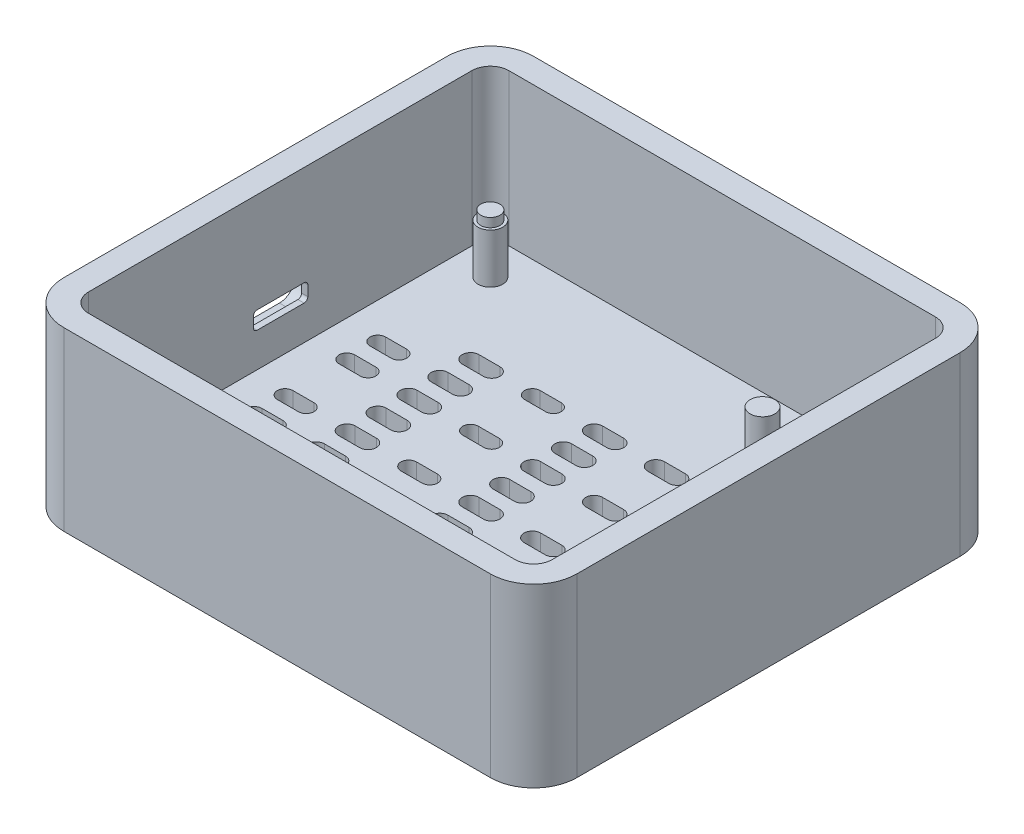
SolidWorks part; units mm, degrees
ref_plane "前视基准面" through (0, 0, 0) normal (0, 0, 1) x (1, 0, 0)
ref_plane "上视基准面" through (0, 0, 0) normal (0, 1, 0) x (1, 0, 0)
ref_plane "右视基准面" through (0, 0, 0) normal (1, 0, 0) x (0, 0, -1)
other "Configuration Table"
sketch "草图1" plane through (0, 0, 0) normal (0, 1, 0) x (1, 0, 0)
  line L1 (-34.5, 34) -> (34.5, 34)
  line L2 (-37.5, 31) -> (-37.5, -31)
  line L3 (-34.5, -34) -> (34.5, -34)
  line L4 (37.5, 31) -> (37.5, -31)
  line L5 (-37.5, 34) -> (37.5, -34) construction
  line L6 (-37.5, -34) -> (37.5, 34) construction
  arc A0 (-34.5, 34) -> (-37.5, 31) centre (-34.5, 31) ccw
  arc A1 (-37.5, -31) -> (-34.5, -34) centre (-34.5, -31) ccw
  arc A2 (34.5, -34) -> (37.5, -31) centre (34.5, -31) ccw
  arc A3 (34.5, 34) -> (37.5, 31) centre (34.5, 31) cw
  point P0 (0, 0)
  dimension "D3" = 3
  dimension "D4" = 3
  dimension "D1" = 75
  dimension "D2" = 68
extrude "凸台-拉伸1" add sketch "草图1" along normal blind 4
sketch "草图2" plane through (0, 4, 0) normal (0, 1, 0) x (1, 0, 0)
  line L0 (-1.709, 0) -> (1.709, 0) construction
  line L1 (-1.709, 1.3428) -> (1.709, 1.3428)
  line L2 (-1.709, -1.3428) -> (1.709, -1.3428)
  line L6 (18.291, 0) -> (21.709, 0) construction
  line L7 (18.291, 1.3428) -> (21.709, 1.3428)
  line L8 (18.291, -1.3428) -> (21.709, -1.3428)
  line L15 (-21.709, 0) -> (-18.291, 0) construction
  line L16 (-21.709, 1.3428) -> (-18.291, 1.3428)
  line L17 (-21.709, -1.3428) -> (-18.291, -1.3428)
  line L21 (-1.709, -5) -> (1.709, -5) construction
  line L22 (-1.709, -3.6572) -> (1.709, -3.6572)
  line L23 (-1.709, -6.3428) -> (1.709, -6.3428)
  line L24 (8.291, -5) -> (11.709, -5) construction
  line L25 (8.291, -3.6572) -> (11.709, -3.6572)
  line L26 (8.291, -6.3428) -> (11.709, -6.3428)
  line L27 (18.291, -5) -> (21.709, -5) construction
  line L28 (18.291, -3.6572) -> (21.709, -3.6572)
  line L29 (18.291, -6.3428) -> (21.709, -6.3428)
  line L30 (28.291, -5) -> (31.709, -5) construction
  line L31 (28.291, -3.6572) -> (31.709, -3.6572)
  line L32 (28.291, -6.3428) -> (31.709, -6.3428)
  line L33 (-11.709, -5) -> (-8.291, -5) construction
  line L34 (-11.709, -3.7386) -> (-8.291, -3.7386)
  line L35 (-11.709, -6.2614) -> (-8.291, -6.2614)
  line L36 (-21.709, -5) -> (-18.291, -5) construction
  line L37 (-21.709, -3.6572) -> (-18.291, -3.6572)
  line L38 (-21.709, -6.3428) -> (-18.291, -6.3428)
  line L39 (-31.709, -5) -> (-28.291, -5) construction
  line L40 (-31.709, -3.7386) -> (-28.291, -3.7386)
  line L41 (-31.709, -6.2614) -> (-28.291, -6.2614)
  line L42 (-1.709, -10) -> (1.709, -10) construction
  line L43 (-1.709, -8.6572) -> (1.709, -8.6572)
  line L44 (-1.709, -11.3428) -> (1.709, -11.3428)
  line L48 (18.291, -10) -> (21.709, -10) construction
  line L49 (18.291, -8.6572) -> (21.709, -8.6572)
  line L50 (18.291, -11.3428) -> (21.709, -11.3428)
  line L51 (28.291, -10) -> (31.709, -10) construction
  line L52 (28.291, -8.6572) -> (31.709, -8.6572)
  line L53 (28.291, -11.3428) -> (31.709, -11.3428)
  line L57 (-21.709, -10) -> (-18.291, -10) construction
  line L58 (-21.709, -8.6572) -> (-18.291, -8.6572)
  line L59 (-21.709, -11.3428) -> (-18.291, -11.3428)
  line L60 (-31.709, -10) -> (-28.291, -10) construction
  line L61 (-31.709, -8.7386) -> (-28.291, -8.7386)
  line L62 (-31.709, -11.2614) -> (-28.291, -11.2614)
  line L63 (-1.709, -15) -> (1.709, -15) construction
  line L64 (-1.709, -13.6572) -> (1.709, -13.6572)
  line L65 (-1.709, -16.3428) -> (1.709, -16.3428)
  line L66 (8.291, -15) -> (11.709, -15) construction
  line L67 (8.291, -13.6572) -> (11.709, -13.6572)
  line L68 (8.291, -16.3428) -> (11.709, -16.3428)
  line L69 (18.291, -15) -> (21.709, -15) construction
  line L70 (18.291, -13.6572) -> (21.709, -13.6572)
  line L71 (18.291, -16.3428) -> (21.709, -16.3428)
  line L75 (-11.709, -15) -> (-8.291, -15) construction
  line L76 (-11.709, -13.7386) -> (-8.291, -13.7386)
  line L77 (-11.709, -16.2614) -> (-8.291, -16.2614)
  line L78 (-21.709, -15) -> (-18.291, -15) construction
  line L79 (-21.709, -13.6572) -> (-18.291, -13.6572)
  line L80 (-21.709, -16.3428) -> (-18.291, -16.3428)
  line L84 (-1.709, 5) -> (1.709, 5) construction
  line L85 (-1.709, 6.3428) -> (1.709, 6.3428)
  line L86 (-1.709, 3.6572) -> (1.709, 3.6572)
  line L87 (8.291, 5) -> (11.709, 5) construction
  line L88 (8.291, 6.3428) -> (11.709, 6.3428)
  line L89 (8.291, 3.6572) -> (11.709, 3.6572)
  line L90 (18.291, 5) -> (21.709, 5) construction
  line L91 (18.291, 6.3428) -> (21.709, 6.3428)
  line L92 (18.291, 3.6572) -> (21.709, 3.6572)
  line L93 (28.291, 5) -> (31.709, 5) construction
  line L94 (28.291, 6.3428) -> (31.709, 6.3428)
  line L95 (28.291, 3.6572) -> (31.709, 3.6572)
  line L96 (-11.709, 5) -> (-8.291, 5) construction
  line L97 (-11.709, 6.2614) -> (-8.291, 6.2614)
  line L98 (-11.709, 3.7386) -> (-8.291, 3.7386)
  line L99 (-21.709, 5) -> (-18.291, 5) construction
  line L100 (-21.709, 6.3428) -> (-18.291, 6.3428)
  line L101 (-21.709, 3.6572) -> (-18.291, 3.6572)
  line L102 (-31.709, 5) -> (-28.291, 5) construction
  line L103 (-31.709, 6.2614) -> (-28.291, 6.2614)
  line L104 (-31.709, 3.7386) -> (-28.291, 3.7386)
  line L105 (-1.709, 10) -> (1.709, 10) construction
  line L106 (-1.709, 11.3428) -> (1.709, 11.3428)
  line L107 (-1.709, 8.6572) -> (1.709, 8.6572)
  line L111 (18.291, 10) -> (21.709, 10) construction
  line L112 (18.291, 11.3428) -> (21.709, 11.3428)
  line L113 (18.291, 8.6572) -> (21.709, 8.6572)
  line L114 (28.291, 10) -> (31.709, 10) construction
  line L115 (28.291, 11.3428) -> (31.709, 11.3428)
  line L116 (28.291, 8.6572) -> (31.709, 8.6572)
  line L120 (-21.709, 10) -> (-18.291, 10) construction
  line L121 (-21.709, 11.3428) -> (-18.291, 11.3428)
  line L122 (-21.709, 8.6572) -> (-18.291, 8.6572)
  line L123 (-31.709, 10) -> (-28.291, 10) construction
  line L124 (-31.709, 11.2614) -> (-28.291, 11.2614)
  line L125 (-31.709, 8.7386) -> (-28.291, 8.7386)
  line L126 (-1.709, 15) -> (1.709, 15) construction
  line L127 (-1.709, 16.3428) -> (1.709, 16.3428)
  line L128 (-1.709, 13.6572) -> (1.709, 13.6572)
  line L129 (8.291, 15) -> (11.709, 15) construction
  line L130 (8.291, 16.3428) -> (11.709, 16.3428)
  line L131 (8.291, 13.6572) -> (11.709, 13.6572)
  line L132 (18.291, 15) -> (21.709, 15) construction
  line L133 (18.291, 16.3428) -> (21.709, 16.3428)
  line L134 (18.291, 13.6572) -> (21.709, 13.6572)
  line L138 (-11.709, 15) -> (-8.291, 15) construction
  line L139 (-11.709, 16.2614) -> (-8.291, 16.2614)
  line L140 (-11.709, 13.7386) -> (-8.291, 13.7386)
  line L141 (-21.709, 15) -> (-18.291, 15) construction
  line L142 (-21.709, 16.3428) -> (-18.291, 16.3428)
  line L143 (-21.709, 13.6572) -> (-18.291, 13.6572)
  line L164 (28.291, 0) -> (31.709, 0) construction
  line L165 (28.291, 1.3428) -> (31.709, 1.3428)
  line L166 (28.291, -1.3428) -> (31.709, -1.3428)
  line L167 (8.291, 0) -> (11.709, 0) construction
  line L168 (8.291, 1.3428) -> (11.709, 1.3428)
  line L169 (8.291, -1.3428) -> (11.709, -1.3428)
  line L170 (-11.709, 0) -> (-8.291, 0) construction
  line L171 (-11.709, 1.3428) -> (-8.291, 1.3428)
  line L172 (-11.709, -1.3428) -> (-8.291, -1.3428)
  line L173 (-31.709, 0) -> (-28.291, 0) construction
  line L174 (-31.709, 1.3428) -> (-28.291, 1.3428)
  line L175 (-31.709, -1.3428) -> (-28.291, -1.3428)
  line L176 (28.291, 0) -> (31.709, 0) construction
  line L177 (28.291, 1.3428) -> (31.709, 1.3428)
  line L178 (28.291, -1.3428) -> (31.709, -1.3428)
  line L179 (8.291, 0) -> (11.709, 0) construction
  line L180 (8.291, 1.3428) -> (11.709, 1.3428)
  line L181 (8.291, -1.3428) -> (11.709, -1.3428)
  line L182 (-11.709, 0) -> (-8.291, 0) construction
  line L183 (-11.709, 1.3428) -> (-8.291, 1.3428)
  line L184 (-11.709, -1.3428) -> (-8.291, -1.3428)
  line L185 (-31.709, 0) -> (-28.291, 0) construction
  line L186 (-31.709, 1.3428) -> (-28.291, 1.3428)
  line L187 (-31.709, -1.3428) -> (-28.291, -1.3428)
  arc A0 (-1.709, 1.3428) -> (-1.709, -1.3428) centre (-1.709, 0) ccw
  arc A1 (1.709, -1.3428) -> (1.709, 1.3428) centre (1.709, 0) ccw
  arc A4 (18.291, 1.3428) -> (18.291, -1.3428) centre (18.291, 0) ccw
  arc A5 (21.709, -1.3428) -> (21.709, 1.3428) centre (21.709, 0) ccw
  arc A10 (-21.709, 1.3428) -> (-21.709, -1.3428) centre (-21.709, 0) ccw
  arc A11 (-18.291, -1.3428) -> (-18.291, 1.3428) centre (-18.291, 0) ccw
  arc A14 (-1.709, -3.6572) -> (-1.709, -6.3428) centre (-1.709, -5) ccw
  arc A15 (1.709, -6.3428) -> (1.709, -3.6572) centre (1.709, -5) ccw
  arc A16 (8.291, -3.6572) -> (8.291, -6.3428) centre (8.291, -5) ccw
  arc A17 (11.709, -6.3428) -> (11.709, -3.6572) centre (11.709, -5) ccw
  arc A18 (18.291, -3.6572) -> (18.291, -6.3428) centre (18.291, -5) ccw
  arc A19 (21.709, -6.3428) -> (21.709, -3.6572) centre (21.709, -5) ccw
  arc A20 (28.291, -3.6572) -> (28.291, -6.3428) centre (28.291, -5) ccw
  arc A21 (31.709, -6.3428) -> (31.709, -3.6572) centre (31.709, -5) ccw
  arc A22 (-11.709, -3.7386) -> (-11.709, -6.2614) centre (-11.709, -5) ccw
  arc A23 (-8.291, -6.2614) -> (-8.291, -3.7386) centre (-8.291, -5) ccw
  arc A24 (-21.709, -3.6572) -> (-21.709, -6.3428) centre (-21.709, -5) ccw
  arc A25 (-18.291, -6.3428) -> (-18.291, -3.6572) centre (-18.291, -5) ccw
  arc A26 (-31.709, -3.7386) -> (-31.709, -6.2614) centre (-31.709, -5) ccw
  arc A27 (-28.291, -6.2614) -> (-28.291, -3.7386) centre (-28.291, -5) ccw
  arc A28 (-1.709, -8.6572) -> (-1.709, -11.3428) centre (-1.709, -10) ccw
  arc A29 (1.709, -11.3428) -> (1.709, -8.6572) centre (1.709, -10) ccw
  arc A32 (18.291, -8.6572) -> (18.291, -11.3428) centre (18.291, -10) ccw
  arc A33 (21.709, -11.3428) -> (21.709, -8.6572) centre (21.709, -10) ccw
  arc A34 (28.291, -8.6572) -> (28.291, -11.3428) centre (28.291, -10) ccw
  arc A35 (31.709, -11.3428) -> (31.709, -8.6572) centre (31.709, -10) ccw
  arc A38 (-21.709, -8.6572) -> (-21.709, -11.3428) centre (-21.709, -10) ccw
  arc A39 (-18.291, -11.3428) -> (-18.291, -8.6572) centre (-18.291, -10) ccw
  arc A40 (-31.709, -8.7386) -> (-31.709, -11.2614) centre (-31.709, -10) ccw
  arc A41 (-28.291, -11.2614) -> (-28.291, -8.7386) centre (-28.291, -10) ccw
  arc A42 (-1.709, -13.6572) -> (-1.709, -16.3428) centre (-1.709, -15) ccw
  arc A43 (1.709, -16.3428) -> (1.709, -13.6572) centre (1.709, -15) ccw
  arc A44 (8.291, -13.6572) -> (8.291, -16.3428) centre (8.291, -15) ccw
  arc A45 (11.709, -16.3428) -> (11.709, -13.6572) centre (11.709, -15) ccw
  arc A46 (18.291, -13.6572) -> (18.291, -16.3428) centre (18.291, -15) ccw
  arc A47 (21.709, -16.3428) -> (21.709, -13.6572) centre (21.709, -15) ccw
  arc A50 (-11.709, -13.7386) -> (-11.709, -16.2614) centre (-11.709, -15) ccw
  arc A51 (-8.291, -16.2614) -> (-8.291, -13.7386) centre (-8.291, -15) ccw
  arc A52 (-21.709, -13.6572) -> (-21.709, -16.3428) centre (-21.709, -15) ccw
  arc A53 (-18.291, -16.3428) -> (-18.291, -13.6572) centre (-18.291, -15) ccw
  arc A56 (-1.709, 6.3428) -> (-1.709, 3.6572) centre (-1.709, 5) ccw
  arc A57 (1.709, 3.6572) -> (1.709, 6.3428) centre (1.709, 5) ccw
  arc A58 (8.291, 6.3428) -> (8.291, 3.6572) centre (8.291, 5) ccw
  arc A59 (11.709, 3.6572) -> (11.709, 6.3428) centre (11.709, 5) ccw
  arc A60 (18.291, 6.3428) -> (18.291, 3.6572) centre (18.291, 5) ccw
  arc A61 (21.709, 3.6572) -> (21.709, 6.3428) centre (21.709, 5) ccw
  arc A62 (28.291, 6.3428) -> (28.291, 3.6572) centre (28.291, 5) ccw
  arc A63 (31.709, 3.6572) -> (31.709, 6.3428) centre (31.709, 5) ccw
  arc A64 (-11.709, 6.2614) -> (-11.709, 3.7386) centre (-11.709, 5) ccw
  arc A65 (-8.291, 3.7386) -> (-8.291, 6.2614) centre (-8.291, 5) ccw
  arc A66 (-21.709, 6.3428) -> (-21.709, 3.6572) centre (-21.709, 5) ccw
  arc A67 (-18.291, 3.6572) -> (-18.291, 6.3428) centre (-18.291, 5) ccw
  arc A68 (-31.709, 6.2614) -> (-31.709, 3.7386) centre (-31.709, 5) ccw
  arc A69 (-28.291, 3.7386) -> (-28.291, 6.2614) centre (-28.291, 5) ccw
  arc A70 (-1.709, 11.3428) -> (-1.709, 8.6572) centre (-1.709, 10) ccw
  arc A71 (1.709, 8.6572) -> (1.709, 11.3428) centre (1.709, 10) ccw
  arc A74 (18.291, 11.3428) -> (18.291, 8.6572) centre (18.291, 10) ccw
  arc A75 (21.709, 8.6572) -> (21.709, 11.3428) centre (21.709, 10) ccw
  arc A76 (28.291, 11.3428) -> (28.291, 8.6572) centre (28.291, 10) ccw
  arc A77 (31.709, 8.6572) -> (31.709, 11.3428) centre (31.709, 10) ccw
  arc A80 (-21.709, 11.3428) -> (-21.709, 8.6572) centre (-21.709, 10) ccw
  arc A81 (-18.291, 8.6572) -> (-18.291, 11.3428) centre (-18.291, 10) ccw
  arc A82 (-31.709, 11.2614) -> (-31.709, 8.7386) centre (-31.709, 10) ccw
  arc A83 (-28.291, 8.7386) -> (-28.291, 11.2614) centre (-28.291, 10) ccw
  arc A84 (-1.709, 16.3428) -> (-1.709, 13.6572) centre (-1.709, 15) ccw
  arc A85 (1.709, 13.6572) -> (1.709, 16.3428) centre (1.709, 15) ccw
  arc A86 (8.291, 16.3428) -> (8.291, 13.6572) centre (8.291, 15) ccw
  arc A87 (11.709, 13.6572) -> (11.709, 16.3428) centre (11.709, 15) ccw
  arc A88 (18.291, 16.3428) -> (18.291, 13.6572) centre (18.291, 15) ccw
  arc A89 (21.709, 13.6572) -> (21.709, 16.3428) centre (21.709, 15) ccw
  arc A92 (-11.709, 16.2614) -> (-11.709, 13.7386) centre (-11.709, 15) ccw
  arc A93 (-8.291, 13.7386) -> (-8.291, 16.2614) centre (-8.291, 15) ccw
  arc A94 (-21.709, 16.3428) -> (-21.709, 13.6572) centre (-21.709, 15) ccw
  arc A95 (-18.291, 13.6572) -> (-18.291, 16.3428) centre (-18.291, 15) ccw
  arc A122 (28.291, 1.3428) -> (28.291, -1.3428) centre (28.291, 0) ccw
  arc A123 (31.709, -1.3428) -> (31.709, 1.3428) centre (31.709, 0) ccw
  arc A124 (8.291, 1.3428) -> (8.291, -1.3428) centre (8.291, 0) ccw
  arc A125 (11.709, -1.3428) -> (11.709, 1.3428) centre (11.709, 0) ccw
  arc A126 (-11.709, 1.3428) -> (-11.709, -1.3428) centre (-11.709, 0) ccw
  arc A127 (-8.291, -1.3428) -> (-8.291, 1.3428) centre (-8.291, 0) ccw
  arc A128 (-31.709, 1.3428) -> (-31.709, -1.3428) centre (-31.709, 0) ccw
  arc A129 (-28.291, -1.3428) -> (-28.291, 1.3428) centre (-28.291, 0) ccw
  point P2 (0, 0)
  point P12 (30, 0)
  point P19 (20, 0)
  point P33 (10, 0)
  point P40 (-20, 0)
  point P47 (-10, 0)
  point P53 (0, -5)
  point P60 (10, -5)
  point P67 (20, -5)
  point P74 (30, -5)
  point P81 (-10, -5)
  point P88 (-20, -5)
  point P95 (-30, -5)
  point P102 (0, -10)
  point P116 (20, -10)
  point P123 (30, -10)
  point P137 (-20, -10)
  point P144 (-30, -10)
  point P151 (0, -15)
  point P158 (10, -15)
  point P165 (20, -15)
  point P170 (0, 0)
  point P173 (-30, -15)
  point P179 (-10, -15)
  point P186 (-20, -15)
  point P191 (0, 0)
  point P194 (30, 15)
  point P200 (0, 5)
  point P207 (10, 5)
  point P214 (20, 5)
  point P221 (30, 5)
  point P228 (-10, 5)
  point P235 (-20, 5)
  point P242 (-30, 5)
  point P249 (0, 10)
  point P263 (20, 10)
  point P270 (30, 10)
  point P284 (-20, 10)
  point P291 (-30, 10)
  point P298 (0, 15)
  point P305 (10, 15)
  point P312 (20, 15)
  point P319 (-30, 0)
  point P326 (-10, 15)
  point P333 (-20, 15)
  point P340 (30, -15)
  point P346 (-30, 15)
  point P355 (30, 0)
  point P362 (10, 0)
  point P369 (-10, 0)
  point P376 (-30, 0)
  point P383 (30, 0)
  point P390 (10, 0)
  point P397 (-10, 0)
  point P404 (-30, 0)
  dimension "D1" = 4
  dimension "D2" = 4
  dimension "D3" = 4
  dimension "D4" = 4
extrude "切除-拉伸1" cut sketch "草图2" against normal blind 65
sketch "草图7" plane through (0, 4, 0) normal (0, 1, 0) x (1, 0, 0)
  line L1 (-36.6213, 33.1213) -> (-31.6213, 33.1213) construction
  line L2 (-36.6213, 33.1213) -> (-36.6213, 28.1213) construction
  line L3 (-36.6213, 28.1213) -> (-31.6213, 28.1213) construction
  line L4 (-31.6213, 33.1213) -> (-31.6213, 28.1213) construction
  line L5 (-36.6213, -33.1213) -> (-31.6213, -33.1213) construction
  line L6 (-36.6213, -33.1213) -> (-36.6213, -28.1213) construction
  line L7 (-36.6213, -28.1213) -> (-31.6213, -28.1213) construction
  line L8 (-31.6213, -33.1213) -> (-31.6213, -28.1213) construction
  arc A0 (-34.5, 34) -> (-37.5, 31) centre (-34.5, 31) ccw construction
  circle A1 centre (-31.6213, 28.1213) radius 2
  arc A2 (-37.5, -31) -> (-34.5, -34) centre (-34.5, -31) ccw construction
  circle A3 centre (-31.6213, -28.1213) radius 2
  dimension "D3" = 5
  dimension "D1" = 5
  dimension "D2" = 5
  dimension "D4" = 5
extrude "凸台-拉伸4" add sketch "草图7" along normal blind 8
sketch "草图8" plane through (0, 12, 0) normal (0, 1, 0) x (1, 0, 0)
  circle A0 centre (-31.6213, -28.1213) radius 1.55
extrude "凸台-拉伸5" add sketch "草图8" along normal blind 1.4618
sketch "草图9" plane through (0, 12, 0) normal (0, 1, 0) x (1, 0, 0)
  circle A0 centre (-31.6213, 28.1213) radius 1.55
extrude "凸台-拉伸6" add sketch "草图9" along normal blind 1.4512
sketch "草图10" plane through (0, 4, 0) normal (0, 1, 0) x (1, 0, 0)
  line L0 (37.5, -31) -> (37.5, 31) construction
  circle A0 centre (16.546, -27.0481) radius 2
  circle A1 centre (16.546, 23.9759) radius 2
  dimension "D1" = 20.954
  dimension "D2" = 20.954
extrude "凸台-拉伸7" add sketch "草图10" along normal blind 8
sketch "草图11" plane through (0, 0, 0) normal (0, -1, 0) x (1, 0, 0)
  line L4 (-34.5, -38) -> (34.5, -38)
  line L5 (41.5, -31) -> (41.5, 31)
  line L6 (34.5, 38) -> (-34.5, 38)
  line L7 (-41.5, 31) -> (-41.5, -31)
  line L8 (-34.5, -34) -> (34.5, -34)
  line L9 (37.5, -31) -> (37.5, 31)
  line L10 (34.5, 34) -> (-34.5, 34)
  line L11 (-37.5, 31) -> (-37.5, -31)
  line L12 (-34.5, -34) -> (34.5, -34)
  line L13 (37.5, -31) -> (37.5, 31)
  line L14 (34.5, 34) -> (-34.5, 34)
  line L15 (-37.5, 31) -> (-37.5, -31)
  arc A4 (-41.5, -31) -> (-34.5, -38) centre (-34.5, -31) ccw
  arc A5 (34.5, -38) -> (41.5, -31) centre (34.5, -31) ccw
  arc A6 (41.5, 31) -> (34.5, 38) centre (34.5, 31) ccw
  arc A7 (-34.5, 38) -> (-41.5, 31) centre (-34.5, 31) ccw
  arc A8 (-37.5, -31) -> (-34.5, -34) centre (-34.5, -31) ccw
  arc A9 (34.5, -34) -> (37.5, -31) centre (34.5, -31) ccw
  arc A10 (37.5, 31) -> (34.5, 34) centre (34.5, 31) ccw
  arc A11 (-34.5, 34) -> (-37.5, 31) centre (-34.5, 31) ccw
  arc A12 (-37.5, -31) -> (-34.5, -34) centre (-34.5, -31) ccw
  arc A13 (34.5, -34) -> (37.5, -31) centre (34.5, -31) ccw
  arc A14 (37.5, 31) -> (34.5, 34) centre (34.5, 31) ccw
  arc A15 (-34.5, 34) -> (-37.5, 31) centre (-34.5, 31) ccw
  dimension "D1" = 0
  dimension "D2" = 4
extrude "凸台-拉伸8" add sketch "草图11" against normal blind 28.55
sketch "草图12" plane through (-41.5, 0, 0) normal (-1, 0, 0) x (0, 0, 1)
  line L2 (-4.189, 9.55) -> (4.046, 9.55) construction
  line L4 (-3.8715, 9.55) -> (3.7285, 9.55)
  line L6 (-4.4715, 9.55) -> (4.3285, 9.55)
  line L7 (-4.4715, 10.15) -> (-4.4715, 11.8)
  line L8 (-3.8715, 12.4) -> (3.7285, 12.4)
  line L9 (4.3285, 10.15) -> (4.3285, 11.8)
  arc A0 (3.7285, 9.55) -> (4.3285, 10.15) centre (3.7285, 10.15) ccw
  arc A1 (-3.8715, 9.55) -> (-4.4715, 10.15) centre (-3.8715, 10.15) cw
  arc A2 (-3.8715, 12.4) -> (-4.4715, 11.8) centre (-3.8715, 11.8) ccw
  arc A3 (3.7285, 12.4) -> (4.3285, 11.8) centre (3.7285, 11.8) cw
  point P0 (-4.189, 9.55)
  point P1 (4.046, 9.55)
  point P13 (-0.0715, 9.55)
  dimension "D1" = 0.6
extrude "切除-拉伸2" cut sketch "草图12" against normal blind 9.55 contours A0 L9 A3 L8 A2 L7 A1 L4
sketch "草图13" plane through (-41.5, 0, 0) normal (-1, 0, 0) x (0, 0, 1)
  line L12 (3.7285, 14.4) -> (-3.8715, 14.4)
  line L13 (6.3285, 10.15) -> (6.3285, 11.8)
  line L14 (-3.8715, 7.55) -> (3.7285, 7.55)
  line L15 (-6.4715, 11.8) -> (-6.4715, 10.15)
  line L16 (3.7285, 14.4) -> (-3.8715, 14.4)
  line L17 (6.3285, 10.15) -> (6.3285, 11.8)
  line L18 (-3.8715, 7.55) -> (3.7285, 7.55)
  line L19 (-6.4715, 11.8) -> (-6.4715, 10.15)
  arc A8 (-3.8715, 14.4) -> (-6.4715, 11.8) centre (-3.8715, 11.8) ccw
  arc A9 (6.3285, 11.8) -> (3.7285, 14.4) centre (3.7285, 11.8) ccw
  arc A10 (3.7285, 7.55) -> (6.3285, 10.15) centre (3.7285, 10.15) ccw
  arc A11 (-6.4715, 10.15) -> (-3.8715, 7.55) centre (-3.8715, 10.15) ccw
  arc A12 (-3.8715, 14.4) -> (-6.4715, 11.8) centre (-3.8715, 11.8) ccw
  arc A13 (6.3285, 11.8) -> (3.7285, 14.4) centre (3.7285, 11.8) ccw
  arc A14 (3.7285, 7.55) -> (6.3285, 10.15) centre (3.7285, 10.15) ccw
  arc A15 (-6.4715, 10.15) -> (-3.8715, 7.55) centre (-3.8715, 10.15) ccw
  point P0 (-6.4715, 10.975)
  point P1 (6.3285, 10.975)
  dimension "D2" = 12.8
  dimension "D1" = 2
extrude "切除-拉伸3" cut sketch "草图13" against normal blind 3 contours A12 L19 A15 L18 A14 L17 A13 L16
